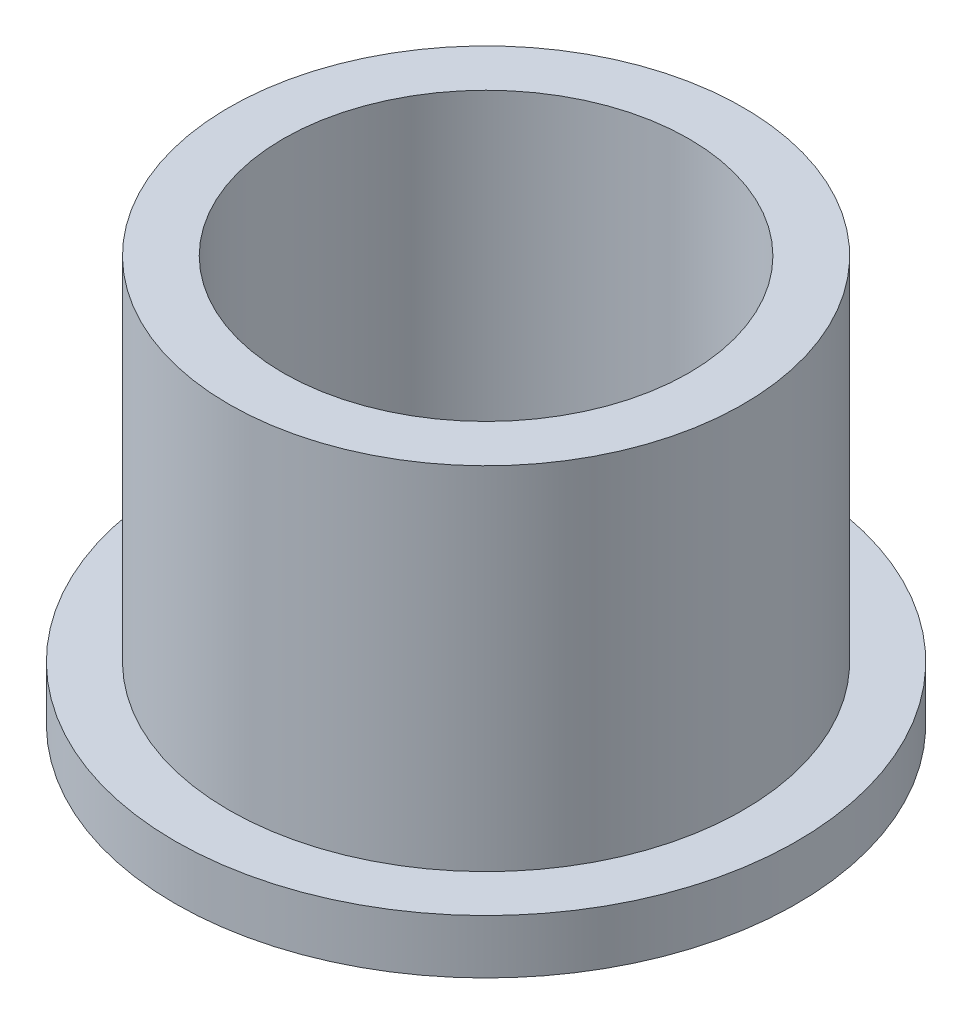
SolidWorks part; units mm, degrees
ref_plane "Front" through (0, 0, 0) normal (0, 0, 1) x (1, 0, 0)
ref_plane "Top" through (0, 0, 0) normal (0, 1, 0) x (1, 0, 0)
ref_plane "Right" through (0, 0, 0) normal (1, 0, 0) x (0, 0, -1)
sketch "Sketch1" plane through (0, 0, 0) normal (0, 1, 0) x (1, 0, 0)
  circle A0 centre (0, 0) radius 15.005
  circle A1 centre (0, 0) radius 19.02
  circle A2 centre (0, 0) radius 23
  dimension "ID" = 30.01
  dimension "OD" = 38.04
  dimension "FlangeOD" = 46
sketch "Sketch2" plane through (0, 0, 0) normal (0, 1, 0) x (1, 0, 0)
  circle A0 centre (0, 0) radius 15.005 construction
  circle A1 centre (0, 0) radius 19.02 construction
  circle A2 centre (0, 0) radius 15.005
  circle A3 centre (0, 0) radius 19.02
extrude "Boss-Extrude1" add sketch "Sketch2" along normal blind 30
sketch "Sketch3" plane through (0, 0, 0) normal (0, 1, 0) x (1, 0, 0)
  circle A0 centre (0, 0) radius 23 construction
  circle A1 centre (0, 0) radius 19.02 construction
  circle A2 centre (0, 0) radius 23
  circle A3 centre (0, 0) radius 19.02
extrude "Boss-Extrude2" add sketch "Sketch3" along normal blind 4
